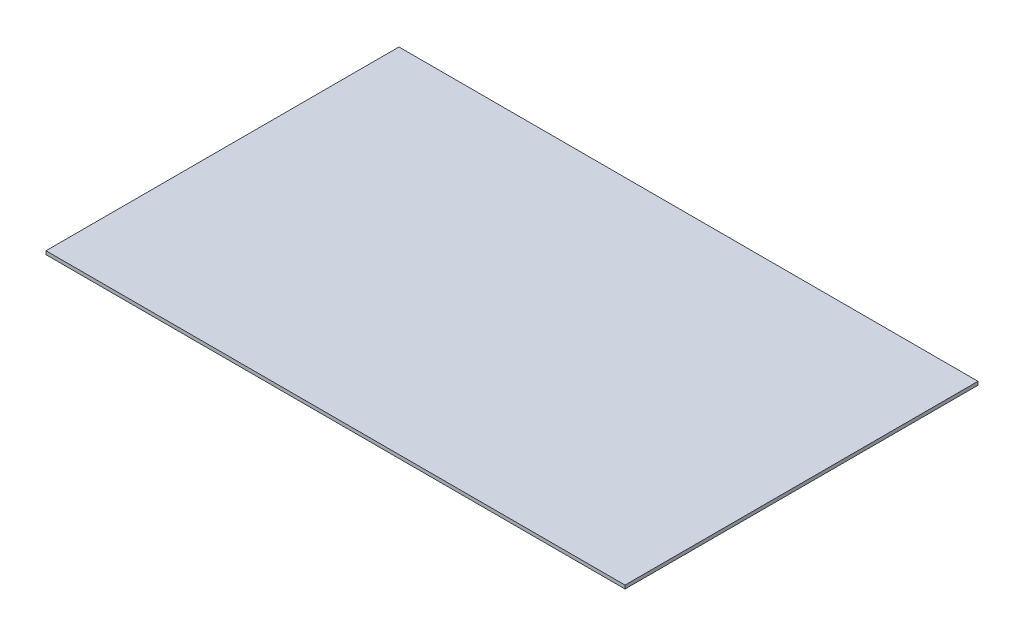
SolidWorks part; units mm, degrees
material "PC High Viscosity"
ref_plane "Front Plane" through (0, 0, 0) normal (0, 0, 1) x (1, 0, 0)
ref_plane "Top Plane" through (0, 0, 0) normal (0, 1, 0) x (1, 0, 0)
ref_plane "Right Plane" through (0, 0, 0) normal (1, 0, 0) x (0, 0, -1)
sketch "Sketch1" plane through (0, 0, 0) normal (0, 1, 0) x (1, 0, 0)
  line L1 (-133.35, 81.28) -> (133.35, 81.28)
  line L2 (-133.35, 81.28) -> (-133.35, -81.28)
  line L3 (-133.35, -81.28) -> (133.35, -81.28)
  line L4 (133.35, 81.28) -> (133.35, -81.28)
  line L5 (-133.35, 81.28) -> (133.35, -81.28) construction
  line L6 (-133.35, -81.28) -> (133.35, 81.28) construction
  point P0 (0, 0)
  dimension "D1" = 266.7
  dimension "D2" = 162.56
extrude "Boss-Extrude1" add sketch "Sketch1" along normal blind 1.5875
